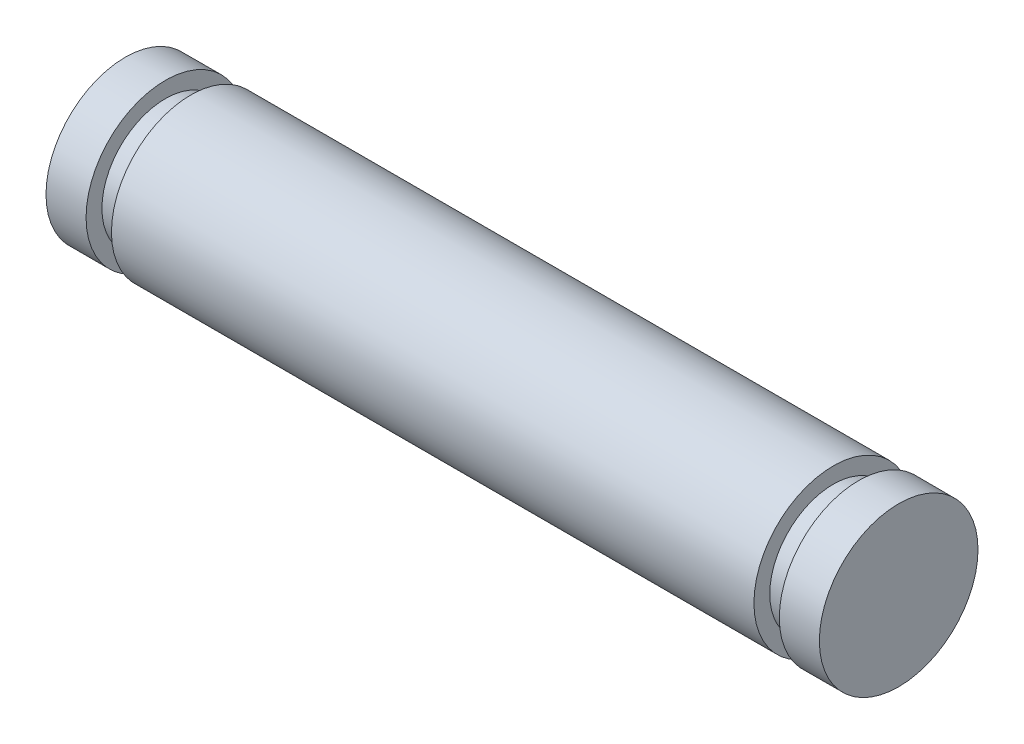
SolidWorks part; units mm, degrees
material "Plain Carbon Steel"
ref_plane "Front Plane" through (0, 0, 0) normal (0, 0, 1) x (1, 0, 0)
ref_plane "Top Plane" through (0, 0, 0) normal (0, 1, 0) x (1, 0, 0)
ref_plane "Right Plane" through (0, 0, 0) normal (1, 0, 0) x (0, 0, -1)
sketch "Sketch1" plane through (0, 0, 0) normal (1, 0, 0) x (0, 0, -1)
  circle A0 centre (0, 0) radius 2
  dimension "D1" = 4
extrude "Boss-Extrude1" add sketch "Sketch1" along normal mid plane 19.5
ref_axis "Axis1" through (-10.725, 0, 0) along (1, 0, 0)
sketch "Sketch2" plane through (0, 0, 0) normal (0, 1, 0) x (1, 0, 0)
  line L0 (9.75, 2) -> (-9.75, 2) construction
  line L1 (-8.74, 2) -> (-8.1, 2)
  line L2 (-8.74, 2) -> (-8.74, 1.6)
  line L3 (-8.74, 1.6) -> (-8.1, 1.6)
  line L4 (-8.1, 2) -> (-8.1, 1.6)
  line L5 (-10.725, 0) -> (10.725, 0) construction
  dimension "D1" = 0.64
  dimension "D2" = 1.6
  dimension "D3" = 8.1
revolve "Cut-Revolve1" cut sketch "Sketch2" angle 360 about axis through (-10.725, 0, 0) along (1, 0, 0)
mirror "Mirror1" about plane through (0, 0, 0) normal (1, 0, 0) of "Cut-Revolve1"
